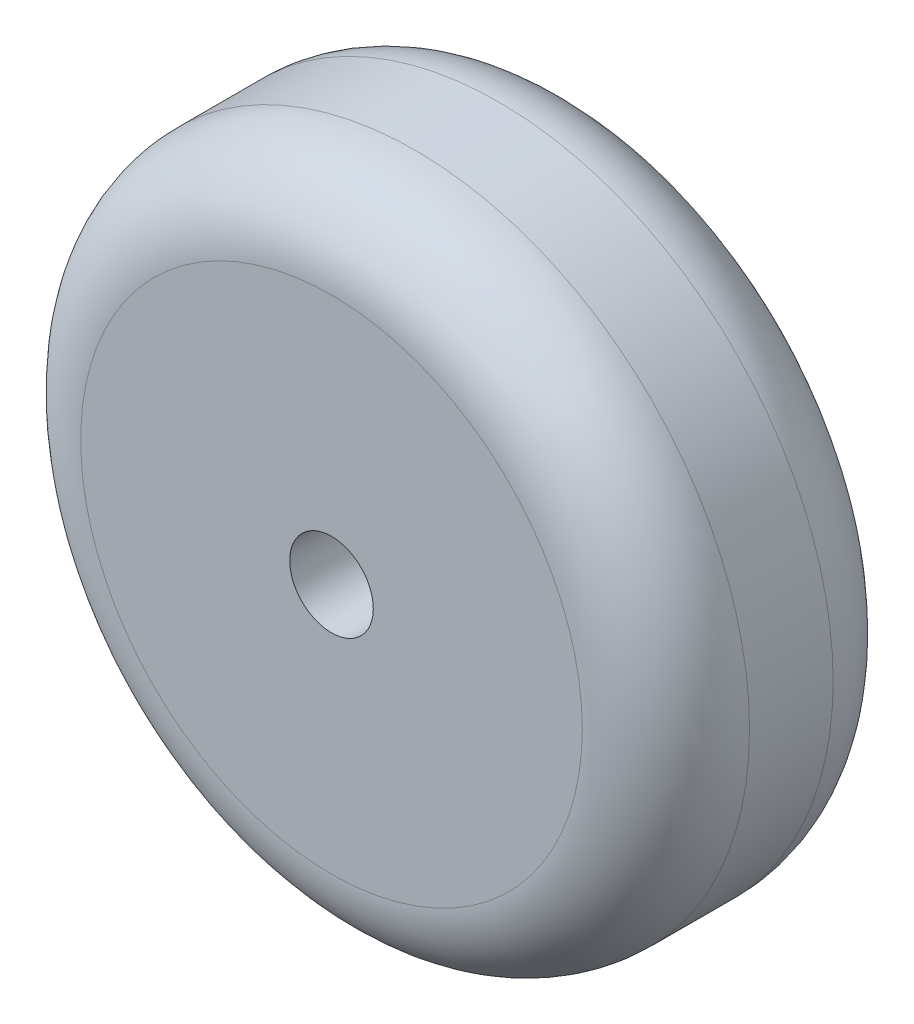
SolidWorks part; units mm, degrees
ref_plane "Front Plane" through (0, 0, 0) normal (0, 0, 1) x (1, 0, 0)
ref_plane "Top Plane" through (0, 0, 0) normal (0, 1, 0) x (1, 0, 0)
ref_plane "Right Plane" through (0, 0, 0) normal (1, 0, 0) x (0, 0, -1)
sketch "Sketch1" plane through (0, 0, 0) normal (0, 0, 1) x (1, 0, 0)
  circle A0 centre (0, 0) radius 40
  dimension "D1" = 80
extrude "Boss-Extrude1" add sketch "Sketch1" along normal blind 30
fillet "Fillet1" radius 10 2 edges at (40, 0, 0) (40, 0, 30)
sketch "Sketch2" plane through (0, 0, 30) normal (0, 0, 1) x (1, 0, 0)
  circle A0 centre (0, 0) radius 5
  dimension "D1" = 10
extrude "Cut-Extrude1" cut sketch "Sketch2" against normal through all both and the other way through all
